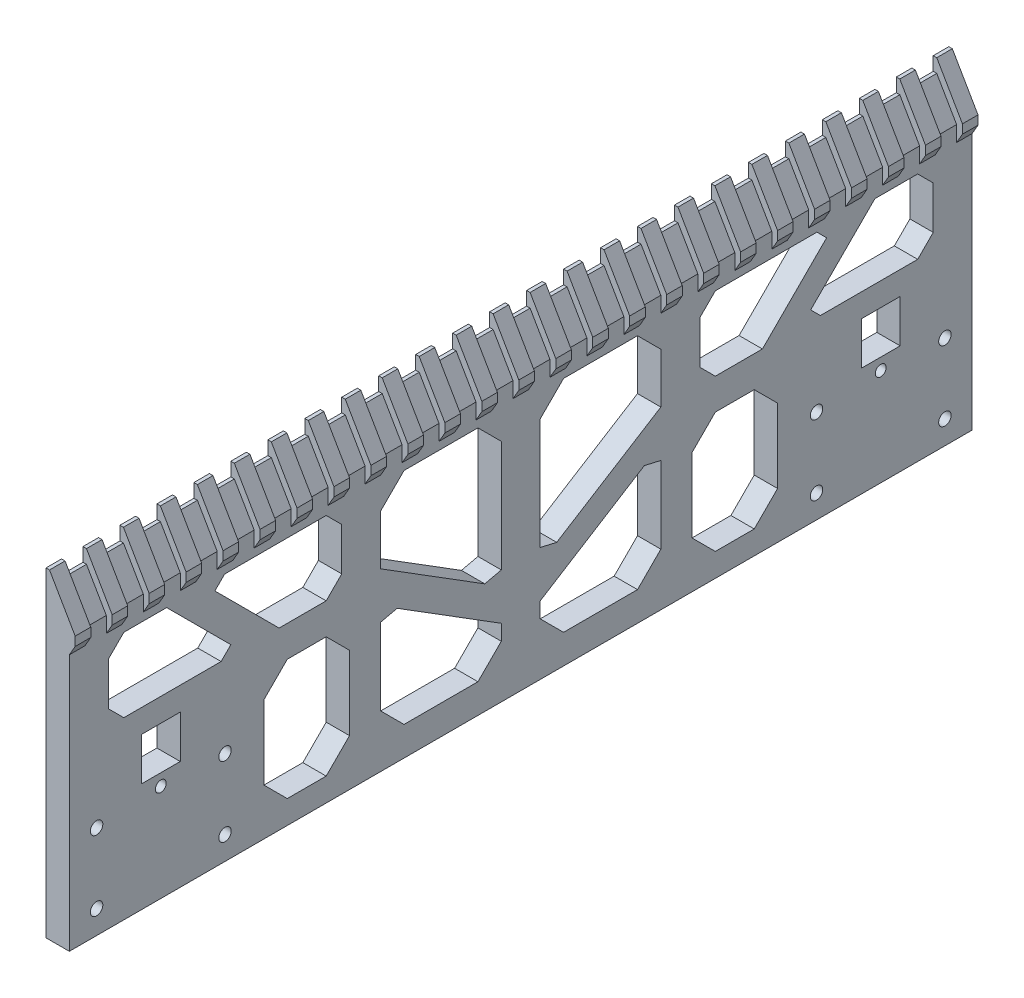
SolidWorks part; units mm, degrees
ref_plane "前视基准面" through (0, 0, 0) normal (0, 0, 1) x (1, 0, 0)
ref_plane "上视基准面" through (0, 0, 0) normal (0, 1, 0) x (1, 0, 0)
ref_plane "右视基准面" through (0, 0, 0) normal (1, 0, 0) x (0, 0, -1)
sketch "草图1" plane through (0, 0, 0) normal (1, 0, 0) x (0, 0, -1)
  line L0 (0, 0) -> (0, -70) construction
  line L1 (-116, 0) -> (116, 0)
  line L2 (-116, 0) -> (-116, -70)
  line L3 (-116, -70) -> (116, -70)
  line L4 (116, 0) -> (116, -70)
  dimension "D1" = 116
  dimension "D2" = 70
extrude "凸台-拉伸1" add sketch "草图1" along normal blind 6
sketch "草图3" plane through (6, 0, 0) normal (1, 0, 0) x (0, 0, -1)
  line L0 (0, 0) -> (0, -70) construction
  line L1 (-102, -6) -> (-91, -6)
  line L2 (-106, -10) -> (-106, -21)
  line L3 (-102, -25) -> (-72, -25)
  line L4 (-46, -10) -> (-46, -21)
  line L5 (116, 0) -> (-116, 0) construction
  line L6 (-116, -70) -> (116, -70) construction
  line L7 (-116, 0) -> (-116, -70) construction
  line L12 (-106, -10) -> (-102, -6)
  line L13 (-106, -21) -> (-102, -25)
  line L14 (-50, -25) -> (-46, -21)
  line L15 (-50, -6) -> (-46, -10)
  line L28 (-36, -12) -> (-30, -6)
  line L36 (-66, -58) -> (-60, -64)
  line L42 (-30, -6) -> (-11, -6)
  line L43 (-36, -12) -> (-36, -24.8748)
  line L44 (-30, -62.5) -> (-11, -62.5)
  line L45 (-5, -12) -> (-5, -44.2458)
  line L46 (-11, -6) -> (-5, -12)
  line L47 (-11, -62.5) -> (-5, -56.5)
  line L48 (-36, -56.5) -> (-30, -62.5)
  line L49 (-60, -33) -> (-50, -33)
  line L50 (-66, -39) -> (-66, -58)
  line L51 (-60, -64) -> (-50, -64)
  line L52 (-44, -39) -> (-44, -58)
  line L53 (-50, -64) -> (-44, -58)
  line L54 (-50, -33) -> (-44, -39)
  line L55 (-66, -39) -> (-60, -33)
  line L56 (-81.1005, -6) -> (-62.1005, -25)
  line L57 (-91, -6) -> (-72, -25)
  line L58 (-91, -6) -> (-81.1005, -6) construction
  line L59 (-81.1005, -6) -> (-50, -6)
  line L60 (-72, -25) -> (-62.1005, -25) construction
  line L61 (-62.1005, -25) -> (-50, -25)
  line L62 (-36, -24.8748) -> (-5, -44.2458)
  line L63 (-5, -52.5) -> (-36, -33.1291)
  line L64 (-5, -44.2458) -> (-5, -52.5) construction
  line L65 (-5, -52.5) -> (-5, -56.5)
  line L66 (-36, -24.8748) -> (-36, -33.1291) construction
  line L67 (-36, -33.1291) -> (-36, -56.5)
  point P0 (-106, -6)
  point P1 (-46, -25)
  point P2 (-106, -25)
  point P3 (-46, -6)
  point P20 (-36, -6)
  point P21 (-5, -62.5)
  point P22 (-36, -62.5)
  point P23 (-5, -6)
  point P24 (-66, -33)
  point P33 (-44, -64)
  point P34 (-66, -64)
  point P35 (-44, -33)
  dimension "D1" = 10
  dimension "D2" = 6
  dimension "D3" = 19
  dimension "D4" = 60
  dimension "D5" = 6
  dimension "D6" = 7.5
  dimension "D7" = 56.5
  dimension "D12" = 80
  dimension "D13" = 5
  dimension "D14" = 31
  dimension "D15" = 10
  dimension "D16" = 8
  dimension "D21" = 8
  dimension "D22" = 31
  dimension "D23" = 22
  dimension "D24" = 7
  dimension "D25" = 45
  dimension "D30" = 34
  dimension "D31" = 7
  dimension "D32" = 10
  dimension "D33" = 58
extrude "切除-拉伸2" cut sketch "草图3" against normal through all
chamfer "倒角1" distance 5 angle 45 4 edges at (3, -33.1291, 36) (3, -44.2458, 5) (3, -6, 81.1005) (3, -25, 72)
sketch "草图2" plane through (0, 0, 0) normal (1, 0, 0) x (0, 0, -1)
  line L0 (-92.5, -26.6289) -> (-92.5, -71.7155) construction
  line L1 (-109, -46) -> (-76, -46) construction
  line L2 (-109, -46) -> (-109, -64) construction
  line L3 (-109, -64) -> (-76, -64) construction
  line L4 (-76, -46) -> (-76, -64) construction
  line L5 (116, 0) -> (-116, 0) construction
  line L6 (0, 0) -> (0, -70) construction
  circle A0 centre (-109, -46) radius 1.55
  circle A1 centre (-76, -64) radius 1.55
  circle A2 centre (-76, -46) radius 1.55
  circle A3 centre (-109, -64) radius 1.55
  point P8 (-92.5, -46)
  dimension "D5" = 3.1
  dimension "D1" = 92.5
  dimension "D2" = 46
  dimension "D3" = 33
  dimension "D4" = 18
sketch "草图6" plane through (0, 0, 116) normal (0, 0, 1) x (1, 0, 0)
  line L0 (6, 0) -> (0, 0)
  line L1 (0, 0) -> (0, 8.8335)
  line L2 (0.9, 8.8335) -> (6, 0)
  line L3 (0, 8.8335) -> (0.9, 8.8335)
  line L4 (0, 8.8335) -> (0, 10.3923) construction
  line L5 (0, 10.3923) -> (0.9, 8.8335) construction
  dimension "D1" = 30
  dimension "D2" = 0.9
extrude "凸台-拉伸2" add sketch "草图6" against normal up to surface (232 mm away) up to face at (3, -35, -116)
ref_plane "基准面1" through (0, 0, 0) normal (0, 0, -1) x (-1, 0, 0)
sketch "草图8" plane through (0, 0, 116) normal (0, 0, 1) x (1, 0, 0)
  line L0 (0, 10.3923) -> (0, 12.3335)
  line L1 (0.9, 12.3335) -> (7.5, 0.9019)
  line L2 (7.5, 0.9019) -> (7.5, -1.4019)
  line L3 (7.5, -4) -> (6, -4) construction
  line L4 (6, 0) -> (6, -70) construction
  line L5 (6, -4) -> (6, 0)
  line L6 (6, 0) -> (0.9, 8.8335) construction
  line L7 (6, 0) -> (0.9, 8.8335)
  line L8 (0, 12.3335) -> (0.9, 12.3335)
  line L9 (0, 12.3335) -> (0, 13.8923) construction
  line L10 (0, 13.8923) -> (0.9, 12.3335) construction
  line L11 (0, 10.3923) -> (0, 8.8335)
  line L12 (0, 8.8335) -> (0.9, 8.8335)
  line L13 (0.9, 8.8335) -> (0, 10.3923) construction
  line L14 (6, -4) -> (7.5, -1.4019)
  line L15 (7.5, -1.4019) -> (7.5, -4) construction
  dimension "D1" = 3.5
  dimension "D2" = 1.5
  dimension "D3" = 4
  dimension "D4" = 0.9
  dimension "D5" = 30
extrude "凸台-拉伸3" add sketch "草图8" against normal blind 4
pattern_linear "阵列(线性)1" count 25 spacing 9.5 along (0, 0, -1) of "凸台-拉伸3"
hole_wizard "打孔尺寸(%根据十字)槽沉头木螺钉的类型1" positions "草图14" profile "草图15" countersink size "M3" standard "GB" end condition through all
sketch "草图14" plane through (0, 0, 0) normal (-1, 0, 0) x (0, 0, 1)
  point P0 (76, -46)
  point P3 (109, -46)
  point P6 (109, -64)
  point P9 (76, -64)
sketch "草图15" plane through (0, -46, 76) normal (0, 1, 0) x (0, 0, 1)
  line L0 (0, 0) -> (0, 7.5)
  line L1 (0, 7.5) -> (1.6, 7.5)
  line L2 (1.6, 7.5) -> (1.6, 1.7)
  line L3 (1.6, 1.7) -> (3.3, 0)
  line L5 (3.3, 0) -> (0, 0)
  line L6 (-1.6, 1.7) -> (-3.3, 0) construction
  line L11 (0, -6.35) -> (0, 107.95) construction
  dimension "通孔孔直径" = 3.2
  dimension "通孔孔深度" = 7.5
  dimension "近端锥形沉头孔直径" = 6.6
  dimension "近端锥形沉头孔角度" = 90
sketch "草图16" plane through (0, 0, 0) normal (-1, 0, 0) x (0, 0, 1)
  line L0 (109, -46) -> (76, -46) construction
  line L2 (116, -70) -> (-116, -70) construction
  line L3 (92.5, -26.6289) -> (92.5, -71.7155) construction
  circle A0 centre (92.5, -45) radius 1.4
  dimension "D1" = 2.8
  dimension "D2" = 25
extrude "切除-拉伸3" cut sketch "草图16" against normal blind 10
mirror "镜向1" about plane through (0, 0, 0) normal (0, 0, -1) of "打孔尺寸(%根据十字)槽沉头木螺钉的类型1"
mirror "镜向2" about plane through (0, 0, 0) normal (0, 0, -1) of "倒角1", "切除-拉伸2", "切除-拉伸3"
sketch "草图17" plane through (0, 0, 0) normal (-1, 0, 0) x (0, 0, 1)
  line L1 (87.5, -31) -> (97.5, -31)
  line L2 (87.5, -31) -> (87.5, -42)
  line L3 (87.5, -42) -> (97.5, -42)
  line L4 (97.5, -31) -> (97.5, -42)
  line L6 (116, -70) -> (-116, -70) construction
  line L7 (0, -70) -> (0, -8.018) construction
  line L8 (-87.5, -31) -> (-97.5, -31)
  line L9 (-87.5, -31) -> (-87.5, -42)
  line L10 (-87.5, -42) -> (-97.5, -42)
  line L11 (-97.5, -31) -> (-97.5, -42)
  line L12 (92.5, -26.6289) -> (92.5, -71.7155) construction
  line L13 (92.5, -26.6289) -> (92.5, -71.7155) construction
  dimension "D1" = 10
  dimension "D2" = 11
  dimension "D4" = 28
extrude "切除-拉伸4" cut sketch "草图17" against normal through all
